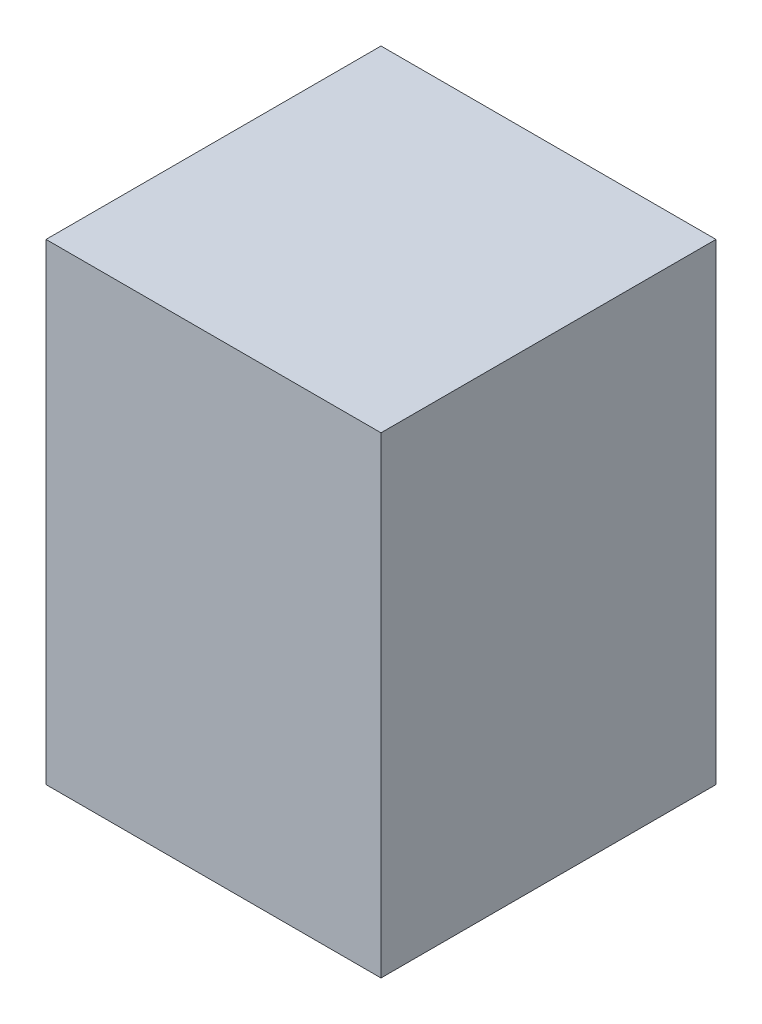
SolidWorks part; units mm, degrees
ref_plane "Front Plane" through (0, 0, 0) normal (0, 0, 1) x (1, 0, 0)
ref_plane "Top Plane" through (0, 0, 0) normal (0, 1, 0) x (1, 0, 0)
ref_plane "Right Plane" through (0, 0, 0) normal (1, 0, 0) x (0, 0, -1)
sketch "Sketch1" plane through (0, 0, 0) normal (0, 1, 0) x (1, 0, 0)
  line L1 (0, 0) -> (10.5, 0)
  line L2 (0, 0) -> (0, 10.5)
  line L3 (0, 10.5) -> (10.5, 10.5)
  line L4 (10.5, 0) -> (10.5, 10.5)
  dimension "D1" = 10.5
  dimension "D2" = 10.5
extrude "Extrude1" add sketch "Sketch1" along normal blind 14.8
ref_plane "Plane1" through (0, 0, 121.5849) normal (0, 0, 1) x (1, 0, 0)
ref_plane "Plane2" through (0, 0, 63.415) normal (0, 0, 1) x (1, 0, 0)
sketch "Sketch2" plane through (0, 0, 0) normal (0, 0, 1) x (1, 0, 0)
  line L0 (0, 7.4) -> (0, 0)
  line L1 (0, 14.8) -> (0, 0) construction
  line L2 (0, 3.7) -> (10.5, 7.4)
  line L3 (10.5, 14.8) -> (10.5, 0) construction
  line L4 (5.25, 5.55) -> (5.039, 6.1489)
  line L5 (5.25, 5.55) -> (5.461, 4.9511)
  spline S0 degree 2 poles (0, 3.7) (4.8279, 6.7478) (10.5, 7.4) knots 0 0 0 1 1 1
  spline S1 degree 2 poles (0, 3.7) (5.6721, 4.3522) (10.5, 7.4) knots 0 0 0 1 1 1
  dimension "D1" = 0.635
  dimension "D2" = 0.635
sketch "Sketch3" plane through (0, 0, 121.5849) normal (0, 0, 1) x (1, 0, 0)
  line L0 (0, 7.4) -> (10.5, 7.4)
  line L1 (5.25, 7.4) -> (5.25, 7.7175)
  line L2 (5.25, 7.4) -> (5.25, 7.0825)
  spline S0 degree 2 poles (0, 7.4) (5.25, 8.035) (10.5, 7.4) knots 0 0 0 1 1 1
  spline S1 degree 2 poles (0, 7.4) (5.25, 6.765) (10.5, 7.4) knots 0 0 0 1 1 1
  dimension "D1" = 0.3175
  dimension "D2" = 0.3175
  dimension "D3" = 10.5
sketch "Sketch4" plane through (0, 0, 63.415) normal (0, 0, 1) x (1, 0, 0)
  line L0 (10.5, 7.4) -> (-20.6399, 1.2059)
  line L1 (0, 7.4) -> (10.5, 7.4) construction
  line L2 (-5.07, 4.3029) -> (-5.1319, 4.6143)
  line L3 (-5.07, 4.3029) -> (-5.008, 3.9915)
  spline S0 degree 2 poles (-20.6399, 1.2059) (-5.1938, 4.9257) (10.5, 7.4) knots 0 0 0 1 1 1
  spline S1 degree 2 poles (10.5, 7.4) (-4.9461, 3.6801) (-20.6399, 1.2059) knots 0 0 0 1 1 1
  dimension "D1" = 31.75
  dimension "D2" = 11.25
  dimension "D3" = 0.3175
  dimension "D4" = 0.3175
ref_plane "Plane3" through (0, 7.4, 0) normal (0, 1, 0) x (-1, 0, 0)
sketch "Sketch5" plane through (0, 7.4, 0) normal (0, 1, 0) x (-1, 0, 0)
  line L0 (0, 121.5849) -> (-10.5, 121.5849) construction
  arc A0 (0, 121.5849) -> (-10.5, 121.5849) centre (-5.25, 121.5849) ccw
equation "\"D2@Sketch1\" = \"D1@Sketch1\""
equation "\"D2@Sketch2\" = \"D1@Sketch2\""
equation "\"D2@Sketch3\" = \"D1@Sketch3\""
equation "\"D4@Sketch4\" = \"D3@Sketch4\""
